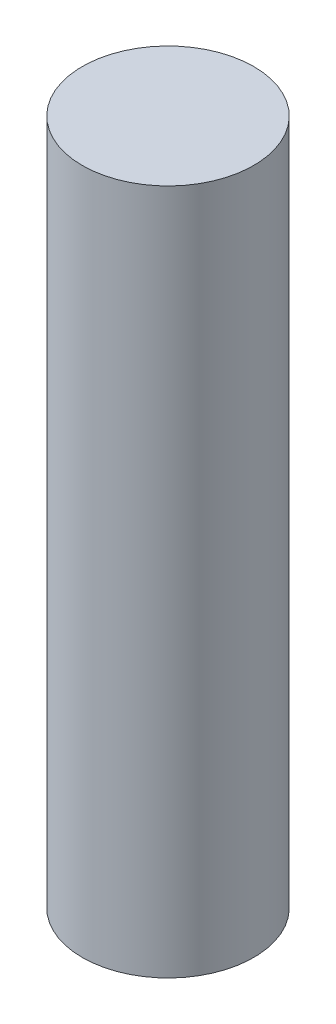
SolidWorks part; units mm, degrees
ref_plane "Front Plane" through (0, 0, 0) normal (0, 0, 1) x (1, 0, 0)
ref_plane "Top Plane" through (0, 0, 0) normal (0, 1, 0) x (1, 0, 0)
ref_plane "Right Plane" through (0, 0, 0) normal (1, 0, 0) x (0, 0, -1)
sketch "Sketch1" plane through (0, 0, 0) normal (0, 0, 1) x (1, 0, 0)
  line L0 (0, 0) -> (0, 50.8) construction
  line L1 (0, 50.8) -> (6.35, 50.8)
  line L2 (6.35, 50.8) -> (6.35, 0)
  line L3 (6.35, 0) -> (0, 0)
  line L4 (0, 0) -> (0, 50.8)
  dimension "D1" = 12.7
  dimension "D2" = 50.8
revolve "Revolve1" add sketch "Sketch1" angle 360 about L0
